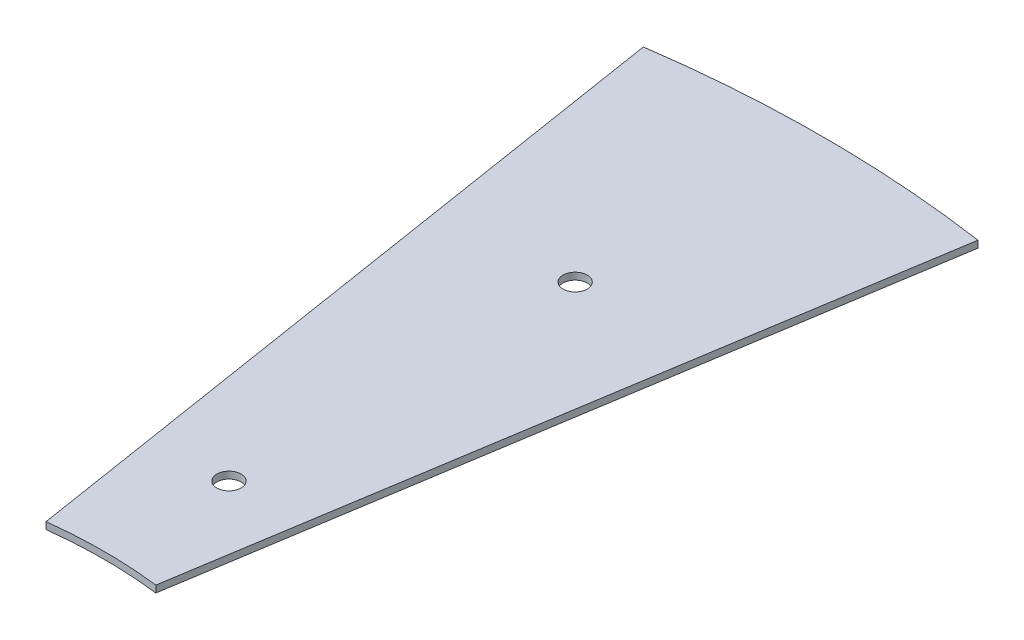
SolidWorks part; units mm, degrees
ref_plane "Front Plane" through (0, 0, 0) normal (0, 0, 1) x (1, 0, 0)
ref_plane "Top Plane" through (0, 0, 0) normal (0, 1, 0) x (1, 0, 0)
ref_plane "Right Plane" through (0, 0, 0) normal (1, 0, 0) x (0, 0, -1)
sketch "Sketch1" plane through (0, 0, 0) normal (0, 1, 0) x (1, 0, 0)
  line L0 (-24.2223, 167.2551) -> (-7.9494, 64.5121)
  line L1 (24.2223, 167.2551) -> (7.9494, 64.5121)
  line L2 (0, 169) -> (0, 0) construction
  arc A0 (-24.2223, 167.2551) -> (24.2223, 167.2551) centre (0, 0) cw
  arc A1 (-7.9494, 64.5121) -> (7.9494, 64.5121) centre (0, 0) cw
  point P0 (7.9494, 64.5121)
  point P7 (0, 169)
  point P8 (0, 65)
  dimension "D3" = 169
  dimension "D4" = 65
  dimension "D1" = 9
  dimension "D2" = 9
extrude "Boss-Extrude1" add sketch "Sketch1" along normal blind 1
sketch "Sketch2" plane through (0, 1, 0) normal (0, 1, 0) x (1, 0, 0)
  line L0 (0, 169) -> (0, 65) construction
  arc A0 (24.2223, 167.2551) -> (-24.2223, 167.2551) centre (0, 0) ccw construction
  arc A1 (7.9494, 64.5121) -> (-7.9494, 64.5121) centre (0, 0) ccw construction
sketch "Sketch3" plane through (0, 0, 0) normal (0, -1, 0) x (1, 0, 0)
  circle A0 centre (0.1968, -82.8452) radius 1.755 construction
  circle A1 centre (0.3156, -132.8451) radius 1.755 construction
  circle A6 centre (0.1968, -82.8452) radius 1.755
  circle A7 centre (0.3156, -132.8451) radius 1.755
extrude "Cut-Extrude2" cut sketch "Sketch3" against normal through all
